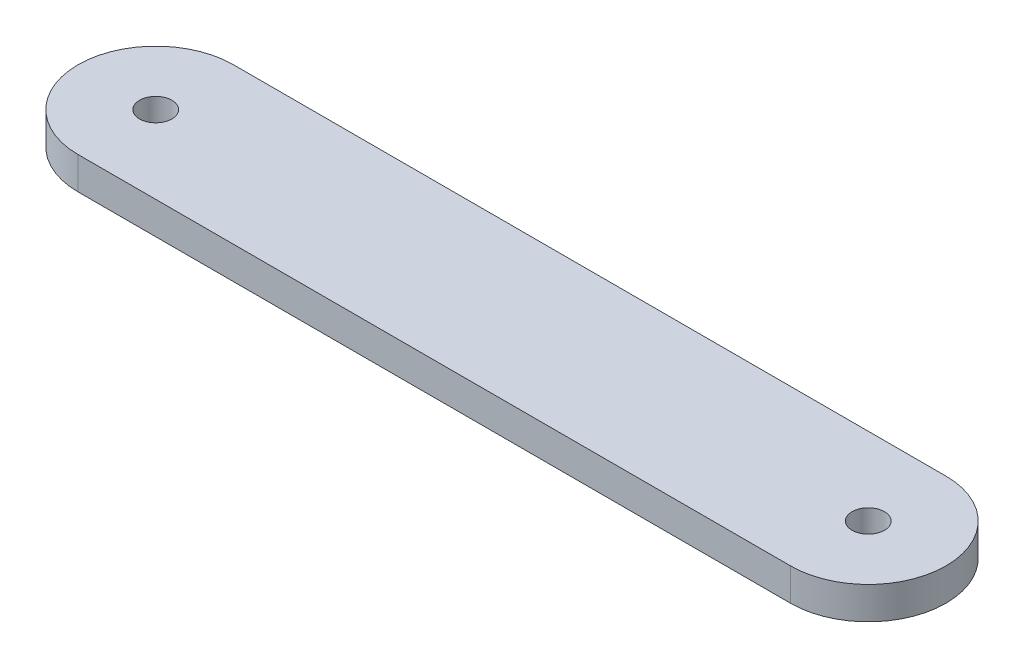
SolidWorks part; units mm, degrees
ref_plane "Спереди" through (0, 0, 0) normal (0, 0, 1) x (1, 0, 0)
ref_plane "Сверху" through (0, 0, 0) normal (0, 1, 0) x (1, 0, 0)
ref_plane "Справа" through (0, 0, 0) normal (1, 0, 0) x (0, 0, -1)
sketch "Эскиз1" plane through (0, 0, 0) normal (0, 1, 0) x (1, 0, 0)
  line L0 (0, 10.1778) -> (110, 10.1778)
  line L1 (0, -13.8222) -> (110, -13.8222)
  circle A0 centre (0, -1.8222) radius 2.5
  arc A1 (0, 10.1778) -> (0, -13.8222) centre (0, -1.8222) ccw
  circle A2 centre (110, -1.8222) radius 2.5
  arc A3 (110, -13.8222) -> (110, 10.1778) centre (110, -1.8222) ccw
  dimension "D1" = 110
extrude "Вытянуть1" add sketch "Эскиз1" along normal blind 5
